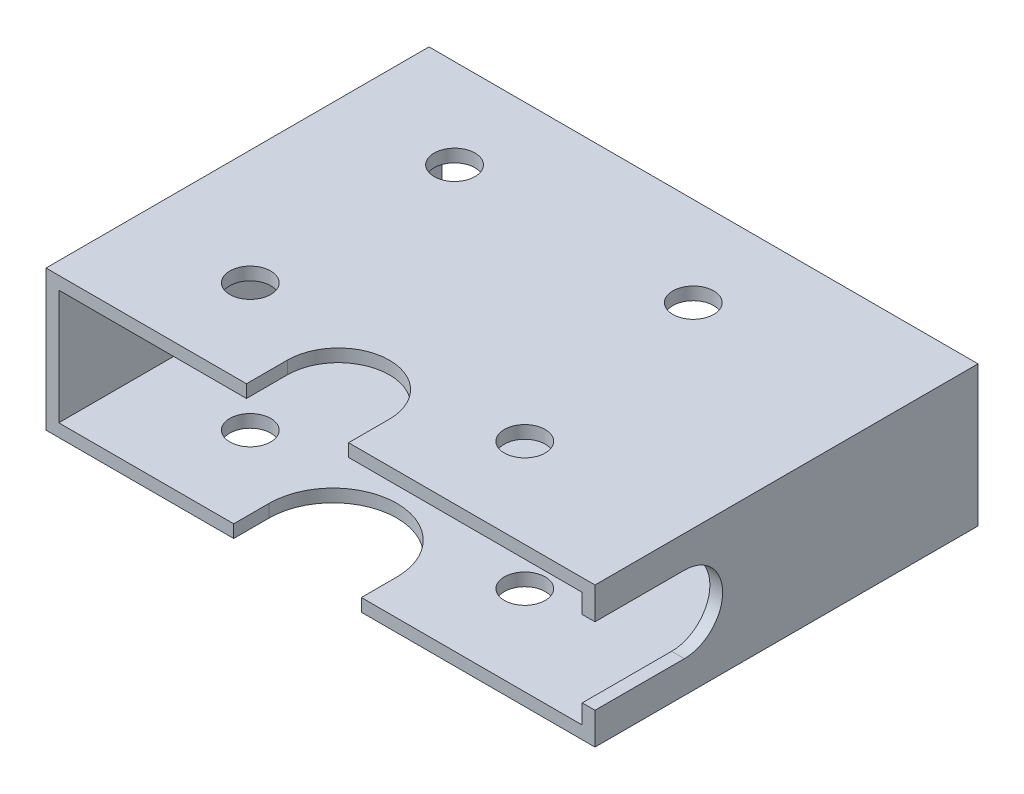
SolidWorks part; units mm, degrees
ref_plane "前视基准面" through (0, 0, 0) normal (0, 0, 1) x (1, 0, 0)
ref_plane "上视基准面" through (0, 0, 0) normal (0, 1, 0) x (1, 0, 0)
ref_plane "右视基准面" through (0, 0, 0) normal (1, 0, 0) x (0, 0, -1)
sketch "草图2" plane through (0, 0, 0) normal (0, 0, 1) x (1, 0, 0)
  line L0 (0, 0) -> (-43, 0)
  line L1 (-43, 0) -> (-43, 11)
  line L2 (-43, 11) -> (0, 11)
  line L3 (0, 11) -> (0, 10)
  line L4 (-1, 10) -> (-42, 10)
  line L5 (-42, 10) -> (-42, 1)
  line L6 (-42, 1) -> (-1, 1)
  line L7 (0, 1) -> (0, 0)
  line L8 (0, 1) -> (0, 10)
  line L9 (-1, 1) -> (-1, 10)
  dimension "D1" = 1
  dimension "D2" = 1
  dimension "D3" = 1
  dimension "D4" = 43
  dimension "D5" = 9
  dimension "D6" = 1
extrude "凸台-拉伸1" add sketch "草图2" along normal blind 30
sketch "草图3" plane through (0, 11, 0) normal (0, 1, 0) x (1, 0, 0)
  line L0 (-43, -30) -> (-43, 0) construction
  line L1 (-43, -15) -> (9.3662, -15) construction
  circle A0 centre (-34, -7) radius 1.6
  circle A1 centre (-34, -23) radius 1.6
  circle A2 centre (-12.5, -23) radius 1.6
  circle A3 centre (-15.3, -7) radius 1.6
  dimension "D1" = 3.2
  dimension "D2" = 9
  dimension "D3" = 21.5
  dimension "D4" = 16
  dimension "D5" = 3.2
  dimension "D6" = 27.7
extrude "切除-拉伸1" cut sketch "草图3" against normal through all
sketch "草图4" plane through (0, 11, 0) normal (0, 1, 0) x (1, 0, 0)
  line L0 (-23.3, -31.0564) -> (-23.3, -14.2185) construction
  line L1 (-43, -30) -> (-43, 0) construction
  line L2 (-27.3, -30) -> (-27.3, -26.8)
  line L3 (0, -30) -> (-43, -30) construction
  line L4 (-19.3, -30) -> (-19.3, -26.8)
  line L5 (-27.3, -30) -> (-19.3, -30)
  arc A0 (-27.3, -26.8) -> (-19.3, -26.8) centre (-23.3, -26.8) cw
  dimension "D3" = 3.2
  dimension "D1" = 19.7
  dimension "D2" = 8
extrude "切除-拉伸2" cut sketch "草图4" against normal blind 2
sketch "草图5" plane through (0, 1, 0) normal (0, 1, 0) x (1, 0, 0)
  line L0 (-23.3, -22.8) -> (-23.3, -31.6414) construction
  line L1 (-28.3, -27.2207) -> (-28.3, -30)
  line L2 (-27.3, -30) -> (-43, -30) construction
  line L3 (-18.3, -27.2207) -> (-18.3, -30)
  line L4 (-28.3, -30) -> (-18.3, -30)
  arc A0 (-19.3, -26.8) -> (-27.3, -26.8) centre (-23.3, -26.8) ccw construction
  arc A1 (-18.3, -27.2207) -> (-28.3, -27.2207) centre (-23.3, -27.2207) ccw
  dimension "D1" = 5
extrude "切除-拉伸3" cut sketch "草图5" against normal blind 10
sketch "草图6" plane through (0, 0, 0) normal (1, 0, 0) x (0, 0, -1)
  line L0 (-30, 5.5) -> (1.1571, 5.5) construction
  line L1 (-30, 0) -> (-30, 11) construction
  line L2 (-23, 8.5) -> (-30, 8.5)
  line L3 (-23, 2.5) -> (-30, 2.5)
  line L4 (-30, 2.5) -> (-30, 8.5)
  arc A0 (-23, 2.5) -> (-23, 8.5) centre (-23, 5.5) ccw
  dimension "D1" = 3
  dimension "D2" = 7
extrude "切除-拉伸4" cut sketch "草图6" against normal blind 10
